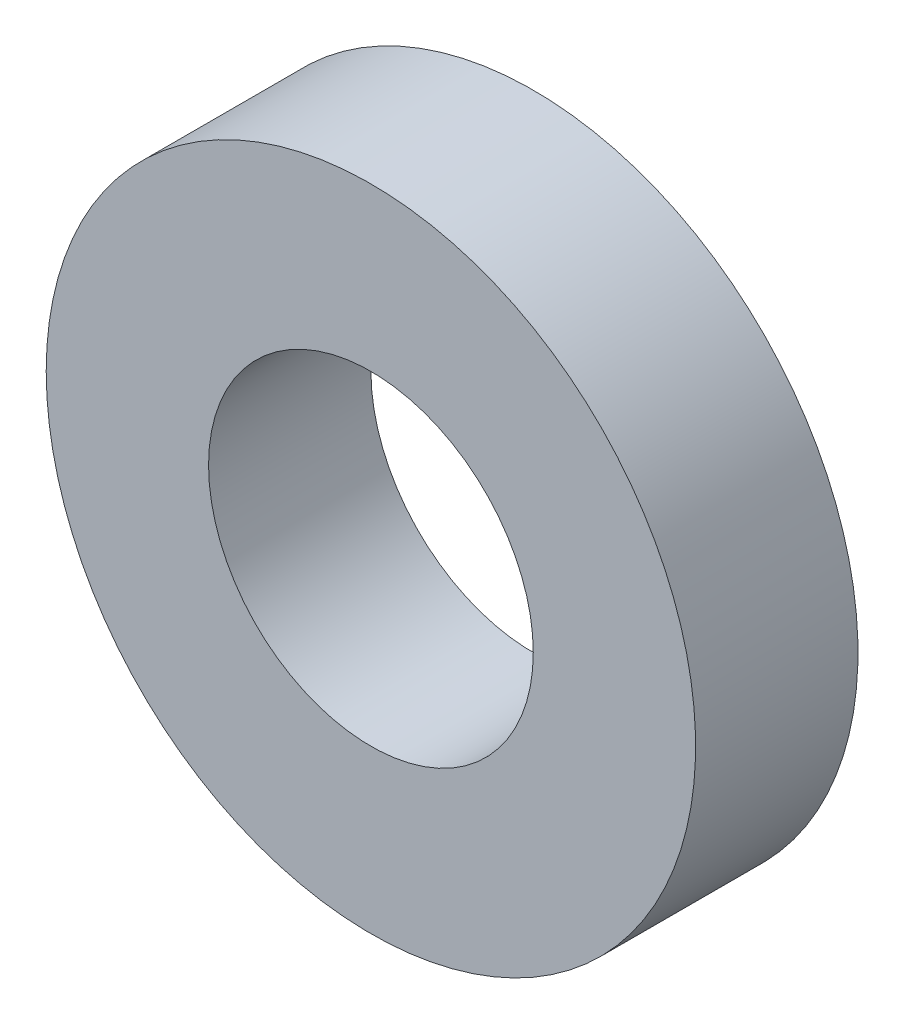
SolidWorks part; units mm, degrees
ref_plane "Front Plane" through (0, 0, 0) normal (0, 0, 1) x (1, 0, 0)
ref_plane "Top Plane" through (0, 0, 0) normal (0, 1, 0) x (1, 0, 0)
ref_plane "Right Plane" through (0, 0, 0) normal (1, 0, 0) x (0, 0, -1)
sketch "Sketch1" plane through (0, 0, 0) normal (0, 0, 1) x (1, 0, 0)
  circle A0 centre (0, 0) radius 5
  circle A1 centre (0, 0) radius 10
  dimension "D1" = 20
  dimension "D2" = 10
extrude "Boss-Extrude2" add sketch "Sketch1" along normal blind 5
